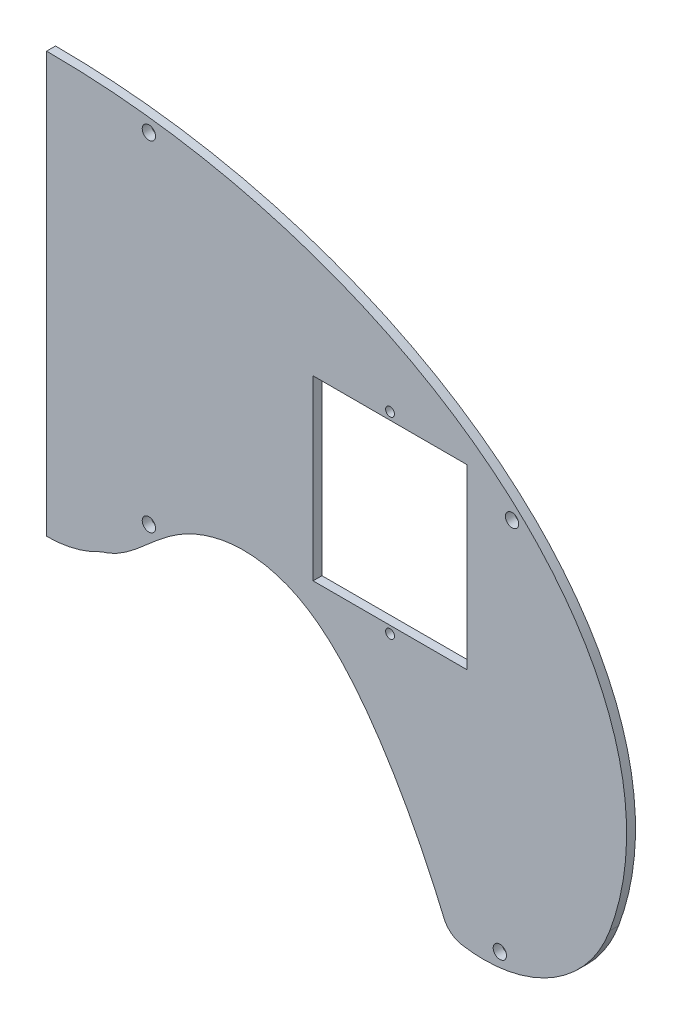
SolidWorks part; units mm, degrees
ref_plane "Alzado" through (0, 0, 0) normal (0, 0, 1) x (1, 0, 0)
ref_plane "Planta" through (0, 0, 0) normal (0, 1, 0) x (1, 0, 0)
ref_plane "Vista lateral" through (0, 0, 0) normal (1, 0, 0) x (0, 0, -1)
sketch "Croquis7" plane through (0, 0, 0) normal (0, 0, 1) x (-1, 0, 0)
  circle A31 centre (-153.1105, 56.1657) radius 2.25
  circle A33 centre (-34.5152, -9.6156) radius 2.25
  circle A35 centre (34.5978, -9.6156) radius 2
  arc A41 (140.3481, 60.5359) -> (134.4676, 56.1109) centre (141.679, 52.6474) ccw
  arc A42 (18.5035, 6.4502) -> (0.0413, 11.1657) centre (0.0413, -27.3343) ccw
  arc A43 (0.0413, 11.1657) -> (-18.4209, 6.4502) centre (0.0413, -27.3343) ccw
  arc A44 (190.316, 31.4795) -> (140.3481, 60.5359) centre (147.8664, 15.9723) ccw
  arc A45 (-134.385, 56.1109) -> (-140.2655, 60.5359) centre (-141.5964, 52.6474) ccw
  circle A47 centre (153.1931, 56.1657) radius 2
  circle A49 centre (-157.2515, -72.2296) radius 2.25
  circle A51 centre (-34.5152, -124.3045) radius 2.25
  circle A53 centre (34.5978, -124.3045) radius 2
  circle A55 centre (157.3341, -71.3124) radius 2
  spline S34 degree 3 poles (134.4676, 56.1109) (134.1497, 55.3341) (133.823, 54.562) (133.1625, 53.0214) (132.8278, 52.2534) (131.8131, 49.9551) (129.7405, 45.3812) (127.5541, 40.867) (124.537, 34.9015) (122.9771, 31.9456) (119.7406, 26.0953) (118.0639, 23.2008) (115.4414, 18.9154) (114.5493, 17.4963) (112.7238, 14.6799) (111.7904, 13.2827) (108.9309, 9.1433) (106.9422, 6.4488) (103.7895, 2.5408) (102.71, 1.2608) (101.0385, -0.6181) (100.4726, -1.2376) (99.3214, -2.461) (98.7352, -3.0657) (96.9496, -4.8484) (95.7253, -5.9925) (93.1935, -8.1717) (91.8856, -9.2063) (89.1637, -11.1369) (87.7504, -12.0335) (85.5424, -13.2632) (84.7899, -13.6545) (83.2733, -14.3869) (82.5072, -14.7293) (80.1852, -15.6842) (78.6055, -16.2244) (76.1869, -16.8847) (75.3725, -17.0799) (73.7268, -17.4186) (72.8936, -17.5624) (68.7052, -18.1459) (65.3663, -18.1723) (61.2066, -17.6857) (60.3753, -17.5622) (58.7142, -17.2624) (57.8851, -17.086) (55.4328, -16.486) (53.8333, -15.9902) (50.7014, -14.8176) (49.1688, -14.1408) (46.9194, -12.9918) (46.1761, -12.5854) (44.7184, -11.7347) (44.0033, -11.2901) (41.8979, -9.9002) (40.5487, -8.8972) (37.9154, -6.8) (36.6314, -5.7052) (34.0802, -3.4945) (32.813, -2.378) (30.2367, -0.2008) (28.9278, 0.8604) (26.2007, 2.837) (24.7825, 3.7527) (22.5133, 4.9374) (21.7312, 5.3009) (20.5388, 5.7796) (20.1373, 5.9286) (19.5289, 6.1355) (19.3251, 6.2018) (18.9151, 6.3283) (18.7092, 6.3889) (18.5035, 6.4502) knots 0 0 0 0 0.015625 0.015625 0.03125 0.03125 0.0625 0.125 0.125 0.1875 0.1875 0.25 0.25 0.28125 0.28125 0.3125 0.3125 0.375 0.375 0.40625 0.40625 0.421875 0.421875 0.4375 0.4375 0.46875 0.46875 0.5 0.5 0.53125 0.53125 0.546875 0.546875 0.5625 0.5625 0.59375 0.59375 0.609375 0.609375 0.625 0.625 0.6875 0.6875 0.703125 0.703125 0.71875 0.71875 0.75 0.75 0.78125 0.78125 0.796875 0.796875 0.8125 0.8125 0.84375 0.84375 0.875 0.875 0.90625 0.90625 0.9375 0.9375 0.96875 0.96875 0.984375 0.984375 0.992188 0.992188 0.996094 0.996094 1 1 1 1
  spline S35 degree 3 poles (0.0413, -130.8343) (6.1345, -130.8343) (18.2614, -130.4542) (30.2709, -129.3262) (42.2211, -127.8206) (48.1667, -126.8792) (59.9963, -124.6051) (65.8805, -123.2725) (74.6576, -120.9611) (79.034, -119.7273) (83.391, -118.3705) (86.2913, -117.4379) (87.7403, -116.9573) (94.9485, -114.4913) (100.6127, -112.3132) (111.7238, -107.5208) (117.1707, -104.9068) (127.8256, -99.1992) (133.0339, -96.1063) (139.3732, -91.8969) (140.6325, -91.0378) (143.1331, -89.2836) (144.3749, -88.388) (148.0522, -85.6602) (150.4464, -83.7821) (157.4477, -77.9604) (161.8749, -73.8302) (168.1008, -67.2053) (170.1073, -64.9256) (173.0021, -61.3872) (173.9479, -60.1879) (175.7992, -57.7476) (176.704, -56.5073) (181.0878, -50.2489) (184.1754, -45.0224) (188.0971, -36.8106) (189.2858, -34.0112) (190.6103, -30.4274) (190.8671, -29.7064) (191.3642, -28.2557) (191.6048, -27.5249) (192.2983, -25.3286) (192.7227, -23.8598) (194.6557, -16.493) (195.5989, -10.5266) (196.0792, -1.4638) (196.0831, 1.576) (195.8454, 6.1652) (195.725, 7.7032) (195.4053, 10.7544) (195.2061, 12.2713) (194.0174, 19.8128) (192.4537, 25.7099) (190.316, 31.4795) knots 0 0 0 0 0.0625 0.125 0.125 0.1875 0.1875 0.25 0.25 0.28125 0.296875 0.296875 0.3125 0.3125 0.375 0.375 0.4375 0.4375 0.5 0.5 0.515625 0.515625 0.53125 0.53125 0.5625 0.5625 0.625 0.625 0.65625 0.65625 0.671875 0.671875 0.6875 0.6875 0.75 0.75 0.78125 0.78125 0.789062 0.789062 0.796875 0.796875 0.8125 0.8125 0.875 0.875 0.90625 0.90625 0.921875 0.921875 0.9375 0.9375 1 1 1 1
  spline S36 degree 3 poles (-190.2396, 31.4627) (-192.3753, 25.6964) (-193.931, 19.8179) (-195.353, 10.8241) (-195.6746, 7.7968) (-195.9176, 3.2095) (-195.9586, 1.6681) (-195.9588, -1.3991) (-195.9184, -2.9265) (-195.5185, -10.5339) (-194.5674, -16.5243) (-192.6293, -23.8987) (-192.204, -25.3678) (-191.5098, -27.5631) (-191.2689, -28.2939) (-190.7708, -29.7454) (-190.5134, -30.4669) (-189.1858, -34.0543) (-187.9935, -36.8588) (-185.3684, -42.3469) (-183.9355, -45.0306) (-181.6166, -48.9709) (-180.8153, -50.2701) (-179.1576, -52.8408) (-178.2995, -54.1146) (-173.8945, -60.3876) (-170.029, -65.0712) (-161.7345, -73.886) (-157.3041, -78.0158) (-151.4553, -82.8734) (-150.2699, -83.8296) (-147.8686, -85.7121) (-146.6511, -86.6395) (-142.9656, -89.3694) (-140.4706, -91.1152) (-132.8814, -96.1488) (-127.6832, -99.2332) (-117.0444, -104.9282) (-111.6035, -107.5381) (-100.5002, -112.325) (-94.8377, -114.5017) (-87.6288, -116.9669) (-86.1801, -117.4472) (-83.2812, -118.3789) (-78.9261, -119.7345) (-74.5518, -120.9675) (-65.7783, -123.2771) (-59.8964, -124.6087) (-48.0711, -126.8813) (-42.1276, -127.8222) (-30.181, -129.3269) (-18.1749, -130.4544) (-6.0508, -130.8343) (0.0413, -130.8343) knots 0 0 0 0 0.0625 0.0625 0.09375 0.09375 0.109375 0.109375 0.125 0.125 0.1875 0.1875 0.203125 0.203125 0.210937 0.210937 0.21875 0.21875 0.25 0.25 0.28125 0.28125 0.296875 0.296875 0.3125 0.3125 0.375 0.375 0.4375 0.4375 0.453125 0.453125 0.46875 0.46875 0.5 0.5 0.5625 0.5625 0.625 0.625 0.6875 0.6875 0.703125 0.703125 0.71875 0.75 0.75 0.8125 0.8125 0.875 0.875 0.9375 1 1 1 1
  spline S37 degree 3 poles (-140.2655, 60.5359) (-142.8693, 60.9752) (-145.4727, 61.1815) (-149.3774, 61.1563) (-150.6788, 61.0918) (-152.6309, 60.9098) (-153.2815, 60.8349) (-154.5828, 60.6562) (-155.2349, 60.5521) (-158.4768, 59.9615) (-160.9933, 59.2705) (-164.6567, 57.918) (-165.8592, 57.4143) (-167.6345, 56.578) (-168.2215, 56.2858) (-169.3859, 55.674) (-169.9645, 55.3537) (-172.8074, 53.6975) (-174.9374, 52.1926) (-177.9226, 49.6738) (-178.8825, 48.7905) (-180.2687, 47.3985) (-180.7218, 46.9233) (-181.6098, 45.9503) (-182.0445, 45.4525) (-184.1498, 42.9327) (-185.6364, 40.7989) (-188.2287, 36.3043) (-189.3345, 33.9434) (-190.2396, 31.4627) knots 0 0 0 0 0.125 0.125 0.1875 0.1875 0.21875 0.21875 0.25 0.25 0.375 0.375 0.4375 0.4375 0.46875 0.46875 0.5 0.5 0.625 0.625 0.6875 0.6875 0.71875 0.71875 0.75 0.75 0.875 0.875 1 1 1 1
  spline S38 degree 3 poles (-18.4209, 6.4502) (-18.6239, 6.3897) (-18.8274, 6.3298) (-19.2315, 6.2052) (-19.4321, 6.1401) (-20.0298, 5.9374) (-20.4228, 5.7921) (-21.5864, 5.3276) (-23.8516, 4.2837) (-25.9572, 2.9439) (-27.9958, 1.4801) (-28.6649, 0.971) (-29.9839, -0.0733) (-31.9328, -1.678) (-33.8306, -3.3482) (-37.6482, -6.6606) (-40.2236, -8.8297) (-43.7321, -11.1693) (-44.4478, -11.6193) (-45.9083, -12.4816) (-46.6541, -12.8941) (-48.91, -14.0595) (-50.4472, -14.7456) (-53.5879, -15.9362) (-55.1916, -16.4402) (-57.65, -17.0517) (-58.4788, -17.2315) (-60.153, -17.5399) (-60.9902, -17.6671) (-65.1772, -18.1706) (-68.5295, -18.1508) (-72.7235, -17.5765) (-73.5654, -17.4332) (-75.2277, -17.0942) (-76.0496, -16.8986) (-78.4886, -16.2359) (-80.0788, -15.693) (-82.4131, -14.7345) (-83.1827, -14.391) (-84.705, -13.6564) (-85.4593, -13.2643) (-87.6863, -12.0236) (-89.1091, -11.119) (-91.846, -9.1738) (-93.1593, -8.1323) (-95.6997, -5.9411) (-96.9266, -4.7914) (-99.3113, -2.4055) (-100.4707, -1.1677) (-102.7053, 1.3503) (-103.7843, 2.6341) (-106.932, 6.544) (-108.9096, 9.2293) (-112.6931, 14.7116) (-114.4983, 17.5091) (-117.9753, 23.1911) (-119.6467, 26.0756) (-122.8791, 31.9168) (-124.4399, 34.8734) (-127.4635, 40.8505) (-128.9258, 43.8693) (-131.0393, 48.4296) (-132.0766, 50.7187) (-133.0806, 53.0229) (-133.7409, 54.5632) (-134.0674, 55.335) (-134.385, 56.1109) knots 0 0 0 0 0.003906 0.003906 0.007812 0.007812 0.015625 0.015625 0.03125 0.0625 0.0625 0.078125 0.078125 0.09375 0.125 0.125 0.1875 0.1875 0.203125 0.203125 0.21875 0.21875 0.25 0.25 0.28125 0.28125 0.296875 0.296875 0.3125 0.3125 0.375 0.375 0.390625 0.390625 0.40625 0.40625 0.4375 0.4375 0.453125 0.453125 0.46875 0.46875 0.5 0.5 0.53125 0.53125 0.5625 0.5625 0.59375 0.59375 0.625 0.625 0.6875 0.6875 0.75 0.75 0.8125 0.8125 0.875 0.875 0.9375 0.9375 0.96875 0.984375 0.984375 1 1 1 1
extrude "Saliente-Extruir5" add sketch "Croquis7" along normal blind 3
sketch "Croquis8" plane through (0, 0, 3) normal (0, 0, 1) x (1, 0, 0)
  line L0 (0, 0) -> (0, 20) construction
  line L2 (-7.1, 27.1) -> (7.1, 27.1)
  line L3 (-7.1, 27.1) -> (-7.1, 12.9)
  line L4 (-7.1, 12.9) -> (7.1, 12.9)
  line L5 (7.1, 27.1) -> (7.1, 12.9)
  line L6 (-7.1, 27.1) -> (7.1, 12.9) construction
  line L7 (-7.1, 12.9) -> (7.1, 27.1) construction
  dimension "D1" = 20
  dimension "D2" = 14.2
extrude "Saliente-Extruir6" add sketch "Croquis8" against normal blind 30
sketch "Croquis9" plane through (0, 0, -27) normal (0, 0, -1) x (-1, 0, 0)
  line L8 (-6.1, 26.1) -> (-6.1, 13.9)
  line L9 (-6.1, 13.9) -> (6.1, 13.9)
  line L10 (6.1, 13.9) -> (6.1, 26.1)
  line L11 (6.1, 26.1) -> (-6.1, 26.1)
  line L12 (-6.1, 26.1) -> (-6.1, 13.9)
  line L13 (-6.1, 13.9) -> (6.1, 13.9)
  line L14 (6.1, 13.9) -> (6.1, 26.1)
  line L15 (6.1, 26.1) -> (-6.1, 26.1)
  dimension "D1" = 1
extrude "Cortar-Extruir3" cut sketch "Croquis9" against normal blind 3.5
sketch "Croquis10" plane through (0, 0, 3) normal (0, 0, 1) x (1, 0, 0)
  line L0 (116, 83.3343) -> (116, 18.3343) construction
  line L2 (90, 80.8343) -> (142, 80.8343)
  line L3 (90, 80.8343) -> (90, 20.8343)
  line L4 (90, 20.8343) -> (142, 20.8343)
  line L5 (142, 80.8343) -> (142, 20.8343)
  line L6 (90, 80.8343) -> (142, 20.8343) construction
  line L7 (90, 20.8343) -> (142, 80.8343) construction
  circle A0 centre (116, 83.3343) radius 1.5
  circle A1 centre (116, 18.3343) radius 1.5
  point P2 (116, 50.8343)
  point P9 (153.1105, -56.1657)
  dimension "D4" = 3
  dimension "D1" = 65
  dimension "D2" = 60
  dimension "D3" = 52
  dimension "D5" = 77
  dimension "D6" = 90
extrude "Cortar-Extruir4" cut sketch "Croquis10" against normal blind 10
sketch "Croquis11" plane through (-7.1, 0, 0) normal (-1, 0, 0) x (0, 0, 1)
  line L0 (0, 20) -> (-7, 20) construction
  line L1 (0, 27.1) -> (0, 12.9) construction
  circle A0 centre (-7, 20) radius 2
  dimension "D1" = 7
  dimension "D2" = 4
extrude "Cortar-Extruir5" cut sketch "Croquis11" against normal through all
sketch "Croquis12" plane through (0, 0, 3) normal (0, 0, 1) x (1, 0, 0)
  line L0 (-0.0413, -11.1657) -> (-0.0413, 130.8343)
  arc A0 (-190.316, -31.4795) -> (-140.3481, -60.5359) centre (-147.8664, -15.9723) ccw construction
  arc A1 (-190.316, -31.4795) -> (-140.3481, -60.5359) centre (-147.8664, -15.9723) ccw
  arc A2 (-140.3481, -60.5359) -> (-134.4676, -56.1109) centre (-141.679, -52.6474) ccw construction
  arc A3 (-140.3481, -60.5359) -> (-134.4676, -56.1109) centre (-141.679, -52.6474) ccw
  arc A4 (-18.5035, -6.4502) -> (18.4209, -6.4502) centre (-0.0413, 27.3343) ccw construction
  arc A5 (-18.5035, -6.4502) -> (-0.0413, -11.1657) centre (-0.0413, 27.3343) ccw
  spline S0 degree 3 poles (1122.2007, -1486.8302) (636.1809, -273.0799) (267.0011, 157.2482) (-30.2709, 129.3262) (-42.2211, 127.8206) (-48.1667, 126.8792) (-59.9963, 124.6051) (-65.8805, 123.2725) (-74.6576, 120.9611) (-79.034, 119.7273) (-83.391, 118.3705) (-86.2913, 117.4379) (-87.7403, 116.9573) (-94.9485, 114.4913) (-100.6127, 112.3132) (-111.7238, 107.5208) (-117.1707, 104.9068) (-127.8256, 99.1992) (-133.0339, 96.1063) (-139.3732, 91.8969) (-140.6325, 91.0378) (-143.1331, 89.2836) (-144.3749, 88.388) (-148.0522, 85.6602) (-150.4464, 83.7821) (-157.4477, 77.9604) (-161.8749, 73.8302) (-168.1008, 67.2053) (-170.1073, 64.9256) (-173.0021, 61.3872) (-173.9479, 60.1879) (-175.7992, 57.7476) (-176.704, 56.5073) (-181.0878, 50.2489) (-184.1754, 45.0224) (-188.0971, 36.8106) (-189.2858, 34.0112) (-190.6103, 30.4274) (-190.8671, 29.7064) (-191.3642, 28.2557) (-191.6048, 27.5249) (-192.2983, 25.3286) (-192.7227, 23.8598) (-194.6557, 16.493) (-195.5989, 10.5266) (-196.0792, 1.4638) (-196.0831, -1.576) (-195.8454, -6.1652) (-195.725, -7.7032) (-195.4053, -10.7544) (-195.2061, -12.2713) (-140.0529, -362.1869) (1958.0495, -256.6598) (-1328.5247, -1347.4453) knots -2.969134 -2.969134 -2.969134 -2.969134 0.0625 0.125 0.125 0.1875 0.1875 0.25 0.25 0.28125 0.296875 0.296875 0.3125 0.3125 0.375 0.375 0.4375 0.4375 0.5 0.5 0.515625 0.515625 0.53125 0.53125 0.5625 0.5625 0.625 0.625 0.65625 0.65625 0.671875 0.671875 0.6875 0.6875 0.75 0.75 0.78125 0.78125 0.789062 0.789062 0.796875 0.796875 0.8125 0.8125 0.875 0.875 0.90625 0.90625 0.921875 0.921875 0.9375 0.9375 4.546761 4.546761 4.546761 4.546761 only from (-0.0413, 130.8343) to (-190.316, -31.4795) construction
  spline S1 degree 3 poles (-0.0413, 130.8343) (-6.1345, 130.8343) (-18.2614, 130.4542) (-30.2709, 129.3262) (-42.2211, 127.8206) (-48.1667, 126.8792) (-59.9963, 124.6051) (-65.8805, 123.2725) (-74.6576, 120.9611) (-79.034, 119.7273) (-83.391, 118.3705) (-86.2913, 117.4379) (-87.7403, 116.9573) (-94.9485, 114.4913) (-100.6127, 112.3132) (-111.7238, 107.5208) (-117.1707, 104.9068) (-127.8256, 99.1992) (-133.0339, 96.1063) (-139.3732, 91.8969) (-140.6325, 91.0378) (-143.1331, 89.2836) (-144.3749, 88.388) (-148.0522, 85.6602) (-150.4464, 83.7821) (-157.4477, 77.9604) (-161.8749, 73.8302) (-168.1008, 67.2053) (-170.1073, 64.9256) (-173.0021, 61.3872) (-173.9479, 60.1879) (-175.7992, 57.7476) (-176.704, 56.5073) (-181.0878, 50.2489) (-184.1754, 45.0224) (-188.0971, 36.8106) (-189.2858, 34.0112) (-190.6103, 30.4274) (-190.8671, 29.7064) (-191.3642, 28.2557) (-191.6048, 27.5249) (-192.2983, 25.3286) (-192.7227, 23.8598) (-194.6557, 16.493) (-195.5989, 10.5266) (-196.0792, 1.4638) (-196.0831, -1.576) (-195.8454, -6.1652) (-195.725, -7.7032) (-195.4053, -10.7544) (-195.2061, -12.2713) (-194.0174, -19.8128) (-192.4537, -25.7099) (-190.316, -31.4795) knots 0 0 0 0 0.0625 0.125 0.125 0.1875 0.1875 0.25 0.25 0.28125 0.296875 0.296875 0.3125 0.3125 0.375 0.375 0.4375 0.4375 0.5 0.5 0.515625 0.515625 0.53125 0.53125 0.5625 0.5625 0.625 0.625 0.65625 0.65625 0.671875 0.671875 0.6875 0.6875 0.75 0.75 0.78125 0.78125 0.789062 0.789062 0.796875 0.796875 0.8125 0.8125 0.875 0.875 0.90625 0.90625 0.921875 0.921875 0.9375 0.9375 1 1 1 1
  spline S2 degree 3 poles (1548.7687, -1131.6078) (-162.0926, -168.8672) (-156.257, -106.8881) (-133.1625, -53.0214) (-132.8278, -52.2534) (-131.8131, -49.9551) (-129.7405, -45.3812) (-127.5541, -40.867) (-124.537, -34.9015) (-122.9771, -31.9456) (-119.7406, -26.0953) (-118.0639, -23.2008) (-115.4414, -18.9154) (-114.5493, -17.4963) (-112.7238, -14.6799) (-111.7904, -13.2827) (-108.9309, -9.1433) (-106.9422, -6.4488) (-103.7895, -2.5408) (-102.71, -1.2608) (-101.0385, 0.6181) (-100.4726, 1.2376) (-99.3214, 2.461) (-98.7352, 3.0657) (-96.9496, 4.8484) (-95.7253, 5.9925) (-93.1935, 8.1717) (-91.8856, 9.2063) (-89.1637, 11.1369) (-87.7504, 12.0335) (-85.5424, 13.2632) (-84.7899, 13.6545) (-83.2733, 14.3869) (-82.5072, 14.7293) (-80.1852, 15.6842) (-78.6055, 16.2244) (-76.1869, 16.8847) (-75.3725, 17.0799) (-73.7268, 17.4186) (-72.8936, 17.5624) (-68.7052, 18.1459) (-65.3663, 18.1723) (-61.2066, 17.6857) (-60.3753, 17.5622) (-58.7142, 17.2624) (-57.8851, 17.086) (-55.4328, 16.486) (-53.8333, 15.9902) (-50.7014, 14.8176) (-49.1688, 14.1408) (-46.9194, 12.9918) (-46.1761, 12.5854) (-44.7184, 11.7347) (-44.0033, 11.2901) (-41.8979, 9.9002) (-40.5487, 8.8972) (-37.9154, 6.8) (-36.6314, 5.7052) (-34.0802, 3.4945) (-32.813, 2.378) (-30.2367, 0.2008) (-28.9278, -0.8604) (-26.2007, -2.837) (-24.7825, -3.7527) (-22.5133, -4.9374) (-21.7312, -5.3009) (-20.5388, -5.7796) (-20.1373, -5.9286) (-19.5289, -6.1355) (-19.3251, -6.2018) (-2.2505, -11.4723) (21.4614, 1.4861) (-674.2407, -1895.5447) knots -1.061414 -1.061414 -1.061414 -1.061414 0.015625 0.015625 0.03125 0.03125 0.0625 0.125 0.125 0.1875 0.1875 0.25 0.25 0.28125 0.28125 0.3125 0.3125 0.375 0.375 0.40625 0.40625 0.421875 0.421875 0.4375 0.4375 0.46875 0.46875 0.5 0.5 0.53125 0.53125 0.546875 0.546875 0.5625 0.5625 0.59375 0.59375 0.609375 0.609375 0.625 0.625 0.6875 0.6875 0.703125 0.703125 0.71875 0.71875 0.75 0.75 0.78125 0.78125 0.796875 0.796875 0.8125 0.8125 0.84375 0.84375 0.875 0.875 0.90625 0.90625 0.9375 0.9375 0.96875 0.96875 0.984375 0.984375 0.992188 0.992188 0.996094 0.996094 1.317606 1.317606 1.317606 1.317606 only from (-134.4676, -56.1109) to (-18.5035, -6.4502) construction
  spline S3 degree 3 poles (-134.4676, -56.1109) (-134.1497, -55.3341) (-133.823, -54.562) (-133.1625, -53.0214) (-132.8278, -52.2534) (-131.8131, -49.9551) (-129.7405, -45.3812) (-127.5541, -40.867) (-124.537, -34.9015) (-122.9771, -31.9456) (-119.7406, -26.0953) (-118.0639, -23.2008) (-115.4414, -18.9154) (-114.5493, -17.4963) (-112.7238, -14.6799) (-111.7904, -13.2827) (-108.9309, -9.1433) (-106.9422, -6.4488) (-103.7895, -2.5408) (-102.71, -1.2608) (-101.0385, 0.6181) (-100.4726, 1.2376) (-99.3214, 2.461) (-98.7352, 3.0657) (-96.9496, 4.8484) (-95.7253, 5.9925) (-93.1935, 8.1717) (-91.8856, 9.2063) (-89.1637, 11.1369) (-87.7504, 12.0335) (-85.5424, 13.2632) (-84.7899, 13.6545) (-83.2733, 14.3869) (-82.5072, 14.7293) (-80.1852, 15.6842) (-78.6055, 16.2244) (-76.1869, 16.8847) (-75.3725, 17.0799) (-73.7268, 17.4186) (-72.8936, 17.5624) (-68.7052, 18.1459) (-65.3663, 18.1723) (-61.2066, 17.6857) (-60.3753, 17.5622) (-58.7142, 17.2624) (-57.8851, 17.086) (-55.4328, 16.486) (-53.8333, 15.9902) (-50.7014, 14.8176) (-49.1688, 14.1408) (-46.9194, 12.9918) (-46.1761, 12.5854) (-44.7184, 11.7347) (-44.0033, 11.2901) (-41.8979, 9.9002) (-40.5487, 8.8972) (-37.9154, 6.8) (-36.6314, 5.7052) (-34.0802, 3.4945) (-32.813, 2.378) (-30.2367, 0.2008) (-28.9278, -0.8604) (-26.2007, -2.837) (-24.7825, -3.7527) (-22.5133, -4.9374) (-21.7312, -5.3009) (-20.5388, -5.7796) (-20.1373, -5.9286) (-19.5289, -6.1355) (-19.3251, -6.2018) (-18.9151, -6.3283) (-18.7092, -6.3889) (-18.5035, -6.4502) knots 0 0 0 0 0.015625 0.015625 0.03125 0.03125 0.0625 0.125 0.125 0.1875 0.1875 0.25 0.25 0.28125 0.28125 0.3125 0.3125 0.375 0.375 0.40625 0.40625 0.421875 0.421875 0.4375 0.4375 0.46875 0.46875 0.5 0.5 0.53125 0.53125 0.546875 0.546875 0.5625 0.5625 0.59375 0.59375 0.609375 0.609375 0.625 0.625 0.6875 0.6875 0.703125 0.703125 0.71875 0.71875 0.75 0.75 0.78125 0.78125 0.796875 0.796875 0.8125 0.8125 0.84375 0.84375 0.875 0.875 0.90625 0.90625 0.9375 0.9375 0.96875 0.96875 0.984375 0.984375 0.992188 0.992188 0.996094 0.996094 1 1 1 1
extrude "Cortar-Extruir6" cut sketch "Croquis12" against normal blind 40 and the other way blind 10
